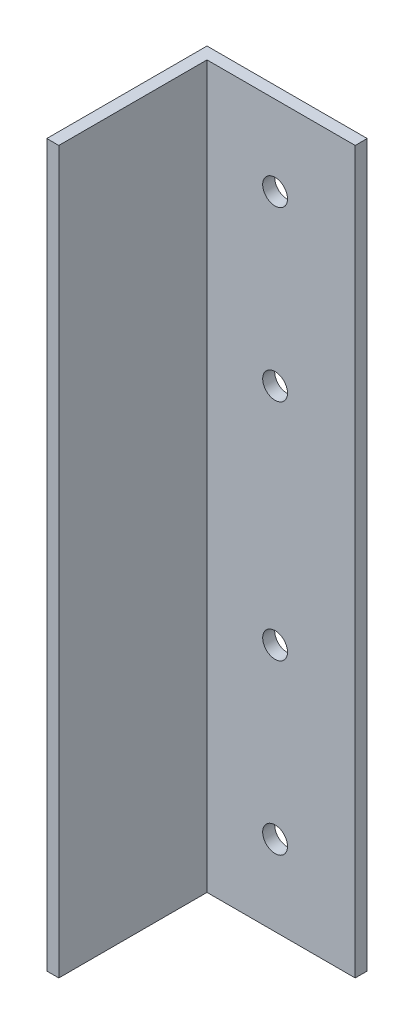
SolidWorks part; units mm, degrees
ref_plane "Front Plane" through (0, 0, 0) normal (0, 0, 1) x (1, 0, 0)
ref_plane "Top Plane" through (0, 0, 0) normal (0, 1, 0) x (1, 0, 0)
ref_plane "Right Plane" through (0, 0, 0) normal (1, 0, 0) x (0, 0, -1)
sketch "Sketch1" plane through (0, 0, 0) normal (0, 0, 1) x (1, 0, 0)
  line L1 (-28, 20.5) -> (-8, 20.5)
  line L2 (-28, 20.5) -> (-28, -69.5)
  line L3 (-28, -69.5) -> (-8, -69.5)
  line L4 (-8, 20.5) -> (-8, -69.5)
  dimension "D1" = 20
  dimension "D2" = 90
extrude "Boss-Extrude1" add sketch "Sketch1" along normal blind 1.5
sketch "Sketch2" plane through (0, 0, 1.5) normal (0, 0, 1) x (1, 0, 0)
  line L0 (-28, -69.5) -> (-8, -69.5) construction
  line L1 (-28, 20.5) -> (-26.5, 20.5)
  line L2 (-28, 20.5) -> (-28, -69.5)
  line L3 (-28, -69.5) -> (-26.5, -69.5)
  line L4 (-26.5, 20.5) -> (-26.5, -69.5)
  dimension "D1" = 1.5
extrude "Boss-Extrude2" add sketch "Sketch2" along normal blind 18.5
sketch "Sketch4" plane through (0, 0, 0) normal (0, 0, -1) x (-1, 0, 0)
  line L0 (18, 20.5) -> (18, -69.5) construction
  line L1 (8, 20.5) -> (28, 20.5) construction
  line L2 (28, -69.5) -> (8, -69.5) construction
  line L3 (8, -69.5) -> (8, 20.5) construction
  circle A0 centre (18, 10.5) radius 1.55
  circle A1 centre (18, -10.5) radius 1.55
  circle A2 centre (18, -59.5) radius 1.55
  circle A3 centre (18, -38.5) radius 1.55
  dimension "D4" = 3.1
  dimension "D1" = 10
  dimension "D2" = 10
  dimension "D3" = 21
  dimension "D5" = 10
  dimension "D6" = 21
extrude "Cut-Extrude1" cut sketch "Sketch4" against normal blind 18.5
